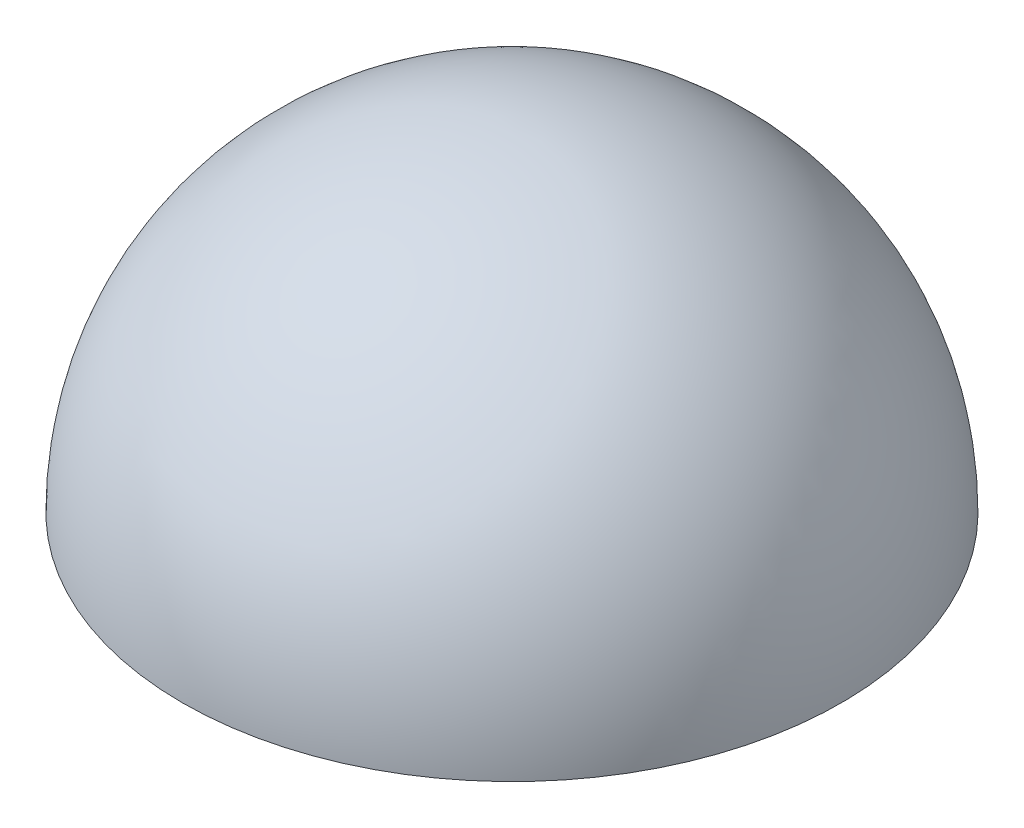
SolidWorks part; units mm, degrees
ref_plane "Front Plane" through (0, 0, 0) normal (0, 0, 1) x (1, 0, 0)
ref_plane "Top Plane" through (0, 0, 0) normal (0, 1, 0) x (1, 0, 0)
ref_plane "Right Plane" through (0, 0, 0) normal (1, 0, 0) x (0, 0, -1)
sketch "Sketch1" plane through (0, 0, 0) normal (0, 1, 0) x (1, 0, 0)
  line L0 (0, 19.05) -> (0, -19.05) construction
  line L1 (0, 19.05) -> (0, -19.05)
  arc A0 (0, -19.05) -> (0, 19.05) centre (0, 0) ccw
revolve "Revolve2" add sketch "Sketch1" angle 180 about L0
